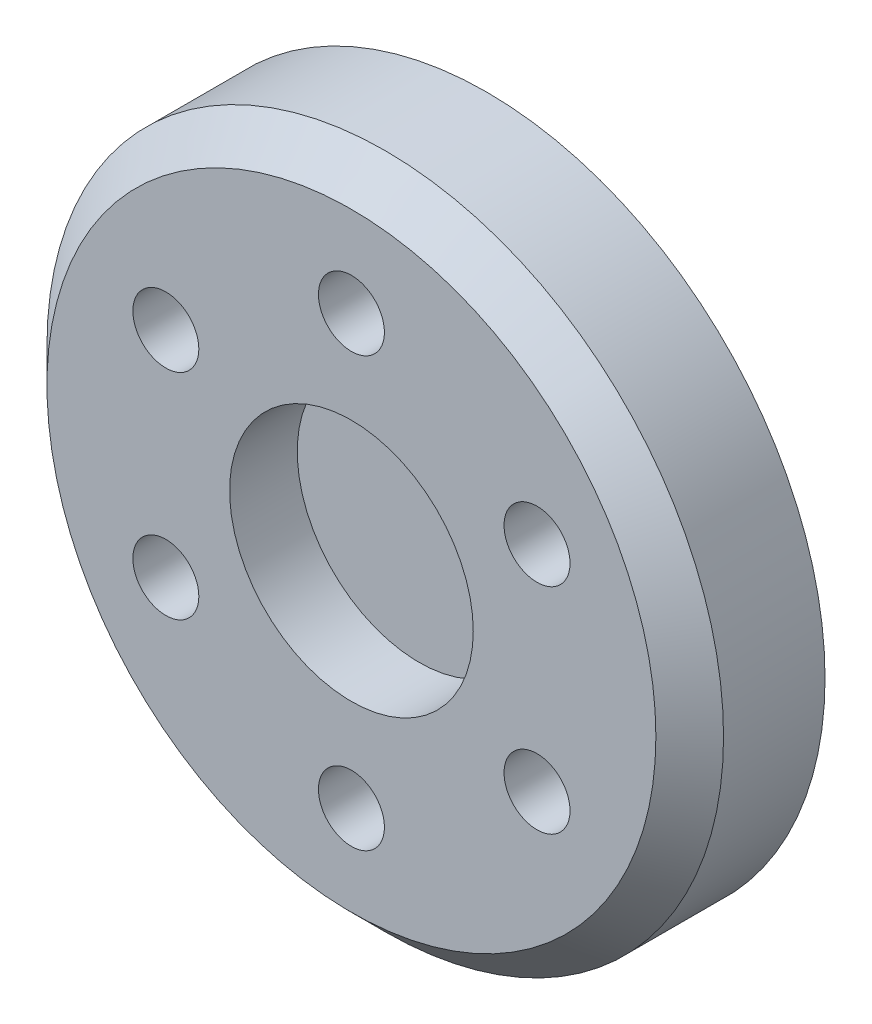
SolidWorks part; units mm, degrees
ref_plane "Front" through (0, 0, 0) normal (0, 0, 1) x (1, 0, 0)
ref_plane "Top" through (0, 0, 0) normal (0, 1, 0) x (1, 0, 0)
ref_plane "Right" through (0, 0, 0) normal (1, 0, 0) x (0, 0, -1)
sketch "Sketch1" plane through (0, 0, 0) normal (0, 0, 1) x (1, 0, 0)
  circle A0 centre (0, 0) radius 15
extrude "Boss-Extrude1" add sketch "Sketch1" along normal blind 20
sketch "Sketch3" plane through (0, 0, 20) normal (0, 0, 1) x (1, 0, 0)
  circle A0 centre (0, 0) radius 50
extrude "Boss-Extrude2" add sketch "Sketch3" along normal blind 20
chamfer "Chamfer1" distance 5 angle 45 1 edges at (50, 0, 40)
sketch "Sketch4" plane through (0, 0, 40) normal (0, 0, 1) x (1, 0, 0)
  circle A0 centre (0, 31.6731) radius 4.8766
  circle A1 centre (0, 0) radius 18.0077
  circle A2 centre (27.4297, 15.8365) radius 4.8766
  circle A3 centre (27.4297, -15.8365) radius 4.8766
  circle A4 centre (0, -31.6731) radius 4.8766
  circle A5 centre (-27.4297, -15.8365) radius 4.8766
  circle A6 centre (-27.4297, 15.8365) radius 4.8766
  point P17 (0, 0)
  dimension "D1" = 6
extrude "Cut-Extrude1" cut sketch "Sketch4" against normal blind 10 contours A2 | A1 | A3 | A4 | A5 | A6 | A0
sketch "Sketch5" plane through (0, 0, 0) normal (0, 0, -1) x (-1, 0, 0)
  circle A0 centre (0, 0) radius 20
  circle A1 centre (0, 0) radius 15 construction
  dimension "D1" = 5
extrude "Boss-Extrude3" add sketch "Sketch5" against normal blind 5
